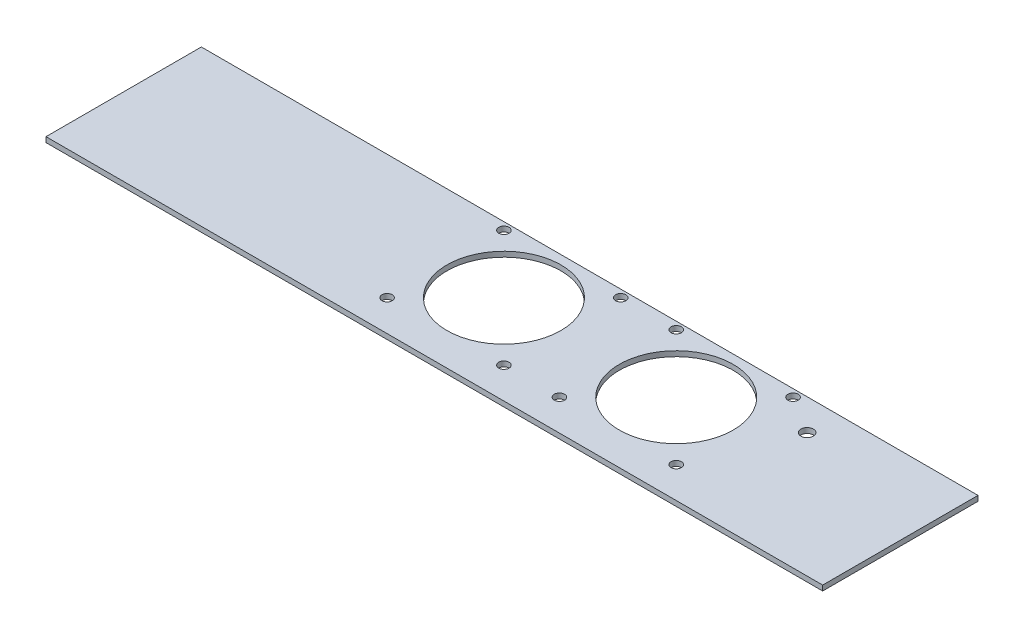
SolidWorks part; units mm, degrees
ref_plane "Front Plane" through (0, 0, 0) normal (0, 0, 1) x (1, 0, 0)
ref_plane "Top Plane" through (0, 0, 0) normal (0, 1, 0) x (1, 0, 0)
ref_plane "Right Plane" through (0, 0, 0) normal (1, 0, 0) x (0, 0, -1)
sketch "Sketch1" plane through (0, 0, 0) normal (0, 0, 1) x (1, 0, 0)
  line L0 (0, 0) -> (0, 381)
  line L5 (0, 381) -> (3.175, 381)
  line L6 (3.175, 381) -> (3.175, 3.175)
  line L7 (3.175, 3.175) -> (473.075, 3.175)
  line L8 (473.075, 3.175) -> (473.075, 0)
  line L9 (473.075, 0) -> (0, 0)
  dimension "D1" = 3.175
  dimension "D2" = 3.175
  dimension "D3" = 381
  dimension "D4" = 473.075
extrude "Boss-Extrude1" add sketch "Sketch1" along normal blind 95.25
sketch "Sketch2" plane through (0, 3.175, 0) normal (0, 1, 0) x (1, 0, 0)
  line L1 (473.075, -95.25) -> (3.175, -95.25) construction
  circle A0 centre (190.119, -4.572) radius 3.175
  circle A1 centre (190.119, -76.2) radius 3.175
  circle A2 centre (261.747, -4.572) radius 3.175
  circle A3 centre (261.747, -76.2) radius 3.175
  circle A4 centre (295.783, -76.2) radius 3.175
  circle A5 centre (295.783, -4.572) radius 3.175
  circle A6 centre (367.411, -76.2) radius 3.175
  circle A7 centre (367.411, -4.572) radius 3.175
  dimension "D3" = 6.35
  dimension "D1" = 6.35
  dimension "D2" = 19.05
  dimension "D4" = 71.628
  dimension "D5" = 71.628
  dimension "D6" = 71.628
  dimension "D7" = 6.35
  dimension "D8" = 6.35
extrude "Cut-Extrude1" cut sketch "Sketch2" against normal blind 152.4
sketch "Sketch4" plane through (0, 0, 0) normal (0, -1, 0) x (1, 0, 0)
  line L0 (473.075, 95.25) -> (473.075, 0) construction
  line L1 (0, 0) -> (473.075, 0) construction
  circle A0 centre (225.933, 40.386) radius 34.925
  circle A1 centre (331.597, 40.386) radius 34.925
  circle A2 centre (390.525, 19.05) radius 3.81
  dimension "D1" = 69.85
  dimension "D2" = 82.55
  dimension "D3" = 19.05
extrude "Cut-Extrude2" cut sketch "Sketch4" against normal blind 381
sketch "Sketch5" plane through (0, 0, 0) normal (-1, 0, 0) x (0, 0, 1)
  line L0 (95.25, 381) -> (0, 381) construction
  line L1 (0, 381) -> (0, 0) construction
  circle A0 centre (19.05, 349.25) radius 3.81
  dimension "D1" = 31.75
  dimension "D2" = 19.05
extrude "Cut-Extrude3" cut sketch "Sketch5" against normal blind 12.7
sketch "Sketch6" plane through (3.175, 0, 0) normal (1, 0, 0) x (0, 0, -1)
  line L1 (0, 381) -> (-95.25, 381)
  line L2 (0, 381) -> (0, 3.175)
  line L3 (0, 3.175) -> (-95.25, 3.175)
  line L4 (-95.25, 381) -> (-95.25, 3.175)
extrude "Cut-Extrude4" cut sketch "Sketch6" against normal through all
sketch "Sketch7" plane through (473.075, 0, 0) normal (1, 0, 0) x (0, 0, -1)
  line L1 (0, 3.175) -> (-95.25, 3.175)
  line L2 (0, 3.175) -> (0, 0)
  line L3 (0, 0) -> (-95.25, 0)
  line L4 (-95.25, 3.175) -> (-95.25, 0)
extrude "Boss-Extrude2" add sketch "Sketch7" along normal blind 3.175
